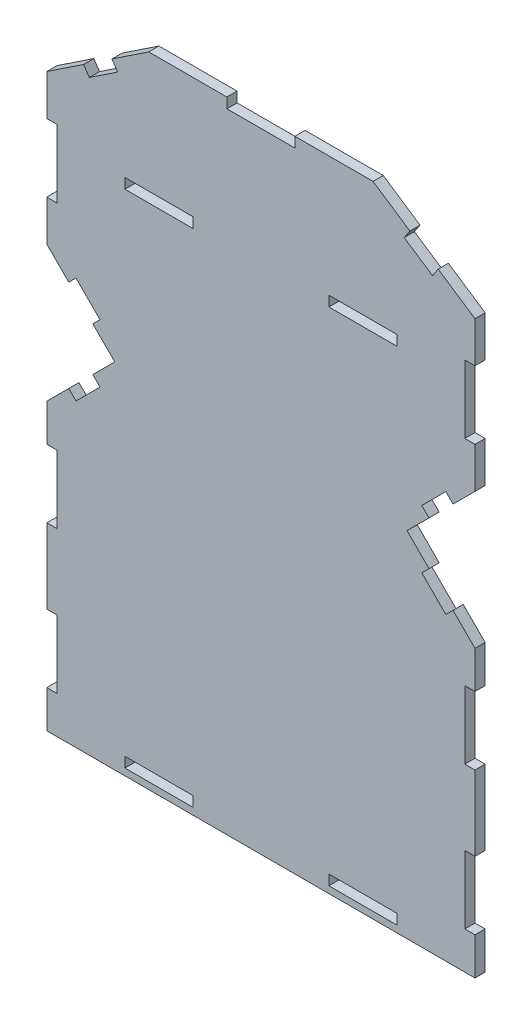
SolidWorks part; units mm, degrees
ref_plane "Front Plane" through (0, 0, 0) normal (0, 0, 1) x (1, 0, 0)
ref_plane "Top Plane" through (0, 0, 0) normal (0, 1, 0) x (1, 0, 0)
ref_plane "Right Plane" through (0, 0, 0) normal (1, 0, 0) x (0, 0, -1)
sketch "Sketch1" plane through (0, 0, 0) normal (0, 0, 1) x (1, 0, 0)
  line L0 (62.2747, 0) -> (62.2747, -11)
  line L1 (-33.7253, 104) -> (-10.7253, 104)
  line L2 (-63.7253, 84) -> (-63.7253, 72)
  line L3 (-63.7253, -84) -> (62.2747, -84)
  line L4 (62.2747, 84) -> (62.2747, 72)
  line L5 (-0.7253, -84) -> (-0.7253, -49.3815) construction
  line L6 (-63.7253, -84) -> (-63.7253, -80.5) construction
  line L7 (-63.7253, -80.5) -> (-60.7253, -80.5) construction
  line L8 (-63.7253, 84) -> (-52.8856, 91.2265)
  line L10 (-63.7253, 84) -> (-63.7253, 72) construction
  line L11 (-60.7253, -80.5) -> (-60.7253, -84) construction
  line L12 (-63.7253, 0) -> (-57.2608, 6.4645)
  line L13 (-43.7253, 20) -> (-50.1898, 26.4645)
  line L14 (62.2747, 0) -> (55.8102, 6.4645)
  line L15 (42.2747, 20) -> (48.7392, 26.4645)
  line L16 (-63.7253, 0) -> (-63.7253, -11)
  line L17 (62.2747, -80.5) -> (59.2747, -80.5) construction
  line L18 (-60.7253, -80.5) -> (59.2747, -80.5) construction
  line L19 (-0.7253, -80.5) -> (-60.7253, -80.5) construction
  line L20 (19.2747, -82) -> (19.2747, -79)
  line L21 (-40.7253, -82) -> (-20.7253, -82)
  line L22 (-40.7253, -82) -> (-40.7253, -79)
  line L23 (-40.7253, -79) -> (-20.7253, -79)
  line L24 (-20.7253, -82) -> (-20.7253, -79)
  line L25 (-40.7253, -82) -> (-20.7253, -79) construction
  line L26 (-40.7253, -79) -> (-20.7253, -82) construction
  line L27 (39.2747, -82) -> (19.2747, -82)
  line L28 (39.2747, -82) -> (39.2747, -79)
  line L29 (39.2747, -79) -> (19.2747, -79)
  line L30 (-63.7253, -84) -> (-62.221, -84) construction
  line L31 (-63.7253, -42) -> (-62.2253, -42) construction
  line L32 (-62.2253, -42) -> (-62.2253, 0) construction
  line L33 (-62.2253, 0) -> (-63.7253, 0) construction
  line L34 (-63.7253, -31) -> (-60.7253, -31)
  line L36 (-63.7253, -11) -> (-60.7253, -11)
  line L37 (-60.7253, -31) -> (-60.7253, -11)
  line L38 (-63.7253, -31) -> (-60.7253, -11) construction
  line L39 (-63.7253, -11) -> (-60.7253, -31) construction
  line L40 (-63.7253, -53) -> (-60.7253, -53)
  line L41 (-60.7253, -53) -> (-60.7253, -73)
  line L42 (-63.7253, -73) -> (-60.7253, -73)
  line L43 (-62.2253, -84) -> (-63.7253, -84) construction
  line L44 (62.2747, -53) -> (59.2747, -53)
  line L45 (59.2747, -53) -> (59.2747, -73)
  line L46 (62.2747, -73) -> (59.2747, -73)
  line L47 (62.2747, -31) -> (59.2747, -31)
  line L48 (62.2747, -11) -> (59.2747, -11)
  line L49 (59.2747, -31) -> (59.2747, -11)
  line L50 (-63.7253, -73) -> (-63.7253, -84)
  line L51 (62.2747, -73) -> (62.2747, -84)
  line L52 (62.2747, -31) -> (62.2747, -53)
  line L53 (-63.7253, -31) -> (-63.7253, -53)
  line L54 (-63.7253, 40) -> (-62.2253, 40) construction
  line L55 (-62.2253, 40) -> (-62.2253, 84) construction
  line L56 (-62.2253, 84) -> (-63.7253, 84) construction
  line L57 (-63.7253, 52) -> (-63.7253, 40)
  line L58 (-63.7253, 52) -> (-60.7253, 52)
  line L60 (-63.7253, 72) -> (-60.7253, 72)
  line L61 (-60.7253, 52) -> (-60.7253, 72)
  line L62 (-63.7253, 52) -> (-60.7253, 72) construction
  line L63 (-63.7253, 72) -> (-60.7253, 52) construction
  line L64 (-63.7253, 52) -> (-63.7253, 40) construction
  line L65 (62.2747, 52) -> (59.2747, 52)
  line L66 (59.2747, 52) -> (59.2747, 72)
  line L67 (62.2747, 72) -> (59.2747, 72)
  line L68 (62.2747, 52) -> (62.2747, 40)
  line L69 (-43.7253, 20) -> (-42.6646, 18.9393) construction
  line L70 (-63.7253, 0) -> (-62.6646, -1.0607) construction
  line L71 (-62.6646, -1.0607) -> (-42.6646, 18.9393) construction
  line L72 (-55.1395, 4.3431) -> (-57.2608, 6.4645)
  line L73 (-55.1395, 4.3431) -> (-48.0685, 11.4142)
  line L75 (-48.0685, 11.4142) -> (-50.1898, 13.5355)
  line L76 (-50.1898, 13.5355) -> (-43.7253, 20)
  line L77 (53.6889, 4.3431) -> (55.8102, 6.4645)
  line L78 (46.6178, 11.4142) -> (48.7392, 13.5355)
  line L79 (53.6889, 4.3431) -> (46.6178, 11.4142)
  line L80 (42.2747, 20) -> (5.8268, 20) construction
  line L81 (-55.1395, 35.6569) -> (-57.2608, 33.5355)
  line L82 (-48.0685, 28.5858) -> (-50.1898, 26.4645)
  line L83 (-55.1395, 35.6569) -> (-48.0685, 28.5858)
  line L84 (-57.2608, 33.5355) -> (-63.7253, 40)
  line L85 (46.6178, 28.5858) -> (48.7392, 26.4645)
  line L86 (53.6889, 35.6569) -> (55.8102, 33.5355)
  line L87 (53.6889, 35.6569) -> (46.6178, 28.5858)
  line L88 (55.8102, 33.5355) -> (62.2747, 40)
  line L89 (48.7392, 13.5355) -> (42.2747, 20)
  line L90 (-63.7253, 84) -> (-52.8856, 91.2265) construction
  line L92 (-52.8856, 91.2265) -> (-51.2215, 88.7303)
  line L93 (-44.5651, 96.7735) -> (-42.901, 94.2774)
  line L94 (-51.2215, 88.7303) -> (-42.901, 94.2774)
  line L95 (-44.5651, 96.7735) -> (-33.7253, 104)
  line L96 (-44.5651, 96.7735) -> (-33.7253, 104) construction
  line L97 (-33.7253, 104) -> (-63.7253, 84) construction
  line L98 (-48.7253, 94) -> (-47.0612, 91.5038) construction
  line L99 (51.4349, 91.2265) -> (49.7708, 88.7303)
  line L100 (49.7708, 88.7303) -> (41.4503, 94.2774)
  line L101 (43.1144, 96.7735) -> (41.4503, 94.2774)
  line L102 (32.2747, 104) -> (43.1144, 96.7735)
  line L103 (62.2747, 84) -> (51.4349, 91.2265)
  line L104 (-33.7253, 104) -> (-33.7253, 102.5) construction
  line L105 (-33.7253, 102.5) -> (32.2747, 102.5) construction
  line L106 (32.2747, 102.5) -> (32.2747, 104) construction
  line L107 (-10.7253, 101) -> (9.2747, 101)
  line L108 (-10.7253, 101) -> (-10.7253, 104)
  line L110 (9.2747, 101) -> (9.2747, 104)
  line L111 (-10.7253, 101) -> (9.2747, 104) construction
  line L112 (-10.7253, 104) -> (9.2747, 101) construction
  line L113 (9.2747, 104) -> (32.2747, 104)
  line L114 (-63.7253, 84) -> (62.2747, 84) construction
  line L115 (-0.7253, 84) -> (-0.7253, 67) construction
  line L116 (-0.7253, 67) -> (-60.7253, 67) construction
  line L117 (39.2747, 65.5) -> (39.2747, 68.5)
  line L118 (-40.7253, 65.5) -> (-20.7253, 65.5)
  line L119 (-40.7253, 65.5) -> (-40.7253, 68.5)
  line L120 (-40.7253, 68.5) -> (-20.7253, 68.5)
  line L121 (-20.7253, 65.5) -> (-20.7253, 68.5)
  line L122 (-40.7253, 65.5) -> (-20.7253, 68.5) construction
  line L123 (-40.7253, 68.5) -> (-20.7253, 65.5) construction
  line L124 (39.2747, 65.5) -> (19.2747, 65.5)
  line L125 (19.2747, 65.5) -> (19.2747, 68.5)
  line L126 (39.2747, 68.5) -> (19.2747, 68.5)
  point P0 (0, 0)
  point P20 (-30.7253, -80.5)
  point P31 (-62.2253, -21)
  point P53 (-62.2253, 62)
  point P67 (-52.6646, 8.9393)
  point P94 (-0.7253, 102.5)
  point P103 (-30.7253, 67)
  dimension "D1" = 84
  dimension "D2" = 126
  dimension "D3" = 20
  dimension "D4" = 30
  dimension "D5" = 20
  dimension "D6" = 20
  dimension "D7" = 44
  dimension "D8" = 20
  dimension "D9" = 30
  dimension "D10" = 20
  dimension "D11" = 20
  dimension "D12" = 84
  dimension "D13" = 44
  dimension "D14" = 20
  dimension "D15" = 3
  dimension "D16" = 3.5
  dimension "D17" = 20
  dimension "D18" = 3
  dimension "D19" = 1.5
  dimension "D20" = 20
  dimension "D21" = 3
  dimension "D22" = 1.5
  dimension "D23" = 1.5
  dimension "D24" = 20
  dimension "D25" = 3
  dimension "D26" = 10
  dimension "D27" = 1.5
  dimension "D28" = 48.0685
  dimension "D29" = 10
  dimension "D30" = 3
  dimension "D31" = 17
  dimension "D32" = 20
  dimension "D33" = 3
  dimension "D34" = 3
  dimension "D35" = 20
  dimension "D36" = 60
extrude "Boss-Extrude1" add sketch "Sketch1" along normal blind 3
